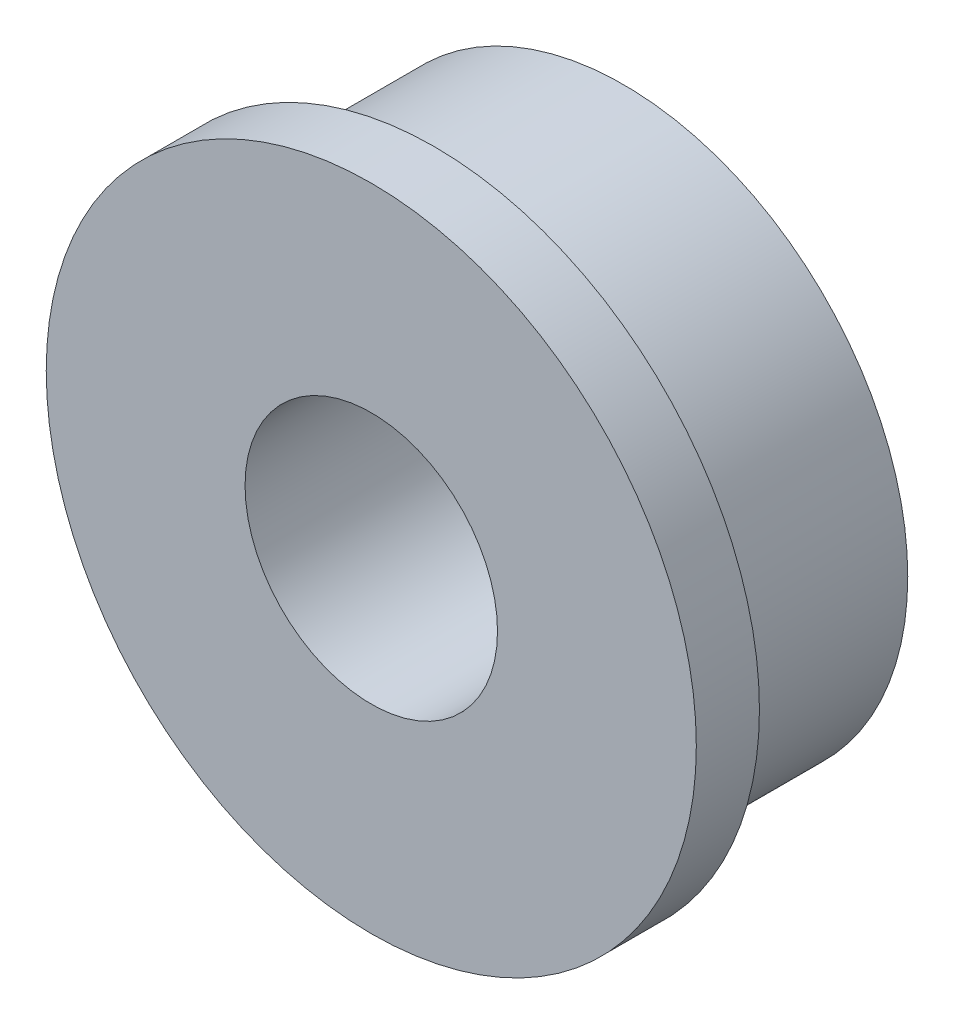
SolidWorks part; units mm, degrees
material "合金钢"
ref_plane "前视基准面" through (0, 0, 0) normal (0, 0, 1) x (1, 0, 0)
ref_plane "上视基准面" through (0, 0, 0) normal (0, 1, 0) x (1, 0, 0)
ref_plane "右视基准面" through (0, 0, 0) normal (1, 0, 0) x (0, 0, -1)
sketch "草图1" plane through (0, 0, 0) normal (0, 0, 1) x (1, 0, 0)
  circle A0 centre (0, 0) radius 2
  circle A1 centre (0, 0) radius 4.5
  dimension "D1" = 4
  dimension "D2" = 9
extrude "凸台-拉伸1" add sketch "草图1" along normal blind 3
sketch "草图2" plane through (0, 0, 3) normal (0, 0, 1) x (1, 0, 0)
  circle A0 centre (0, 0) radius 5.15
  circle A1 centre (0, 0) radius 2
  dimension "D1" = 10.3
  dimension "D2" = 4
extrude "凸台-拉伸2" add sketch "草图2" along normal blind 1
